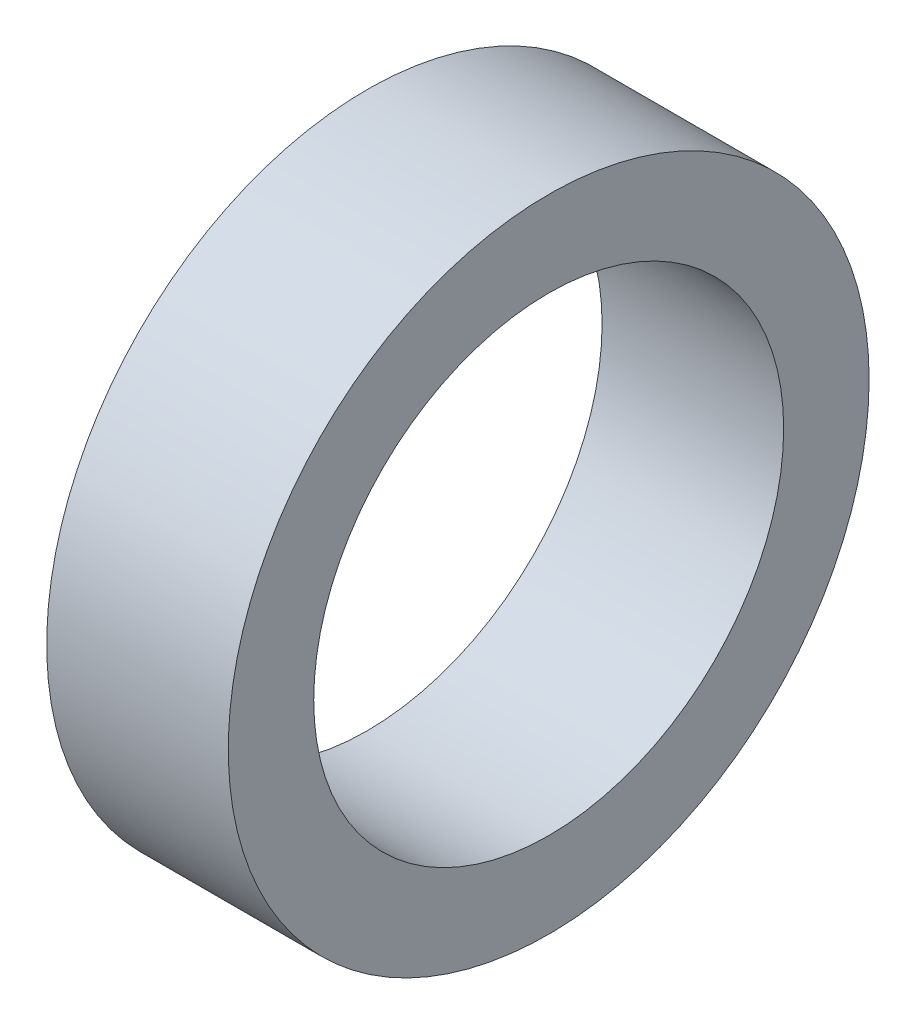
SolidWorks part; units mm, degrees
material "Полиуретан (11671)"
ref_plane "Спереди" through (0, 0, 0) normal (0, 0, 1) x (1, 0, 0)
ref_plane "Сверху" through (0, 0, 0) normal (0, 1, 0) x (1, 0, 0)
ref_plane "Справа" through (0, 0, 0) normal (1, 0, 0) x (0, 0, -1)
sketch "Эскиз1" plane through (0, 0, 0) normal (0, 0, 1) x (1, 0, 0)
  line L0 (-34, 60) -> (-34, 44)
  line L1 (-34, 44) -> (0, 44)
  line L2 (0, 44) -> (0, 60)
  line L3 (0, 60) -> (-34, 60)
  line L4 (-34, 0) -> (0, 0) construction
revolve "Повернуть1" add sketch "Эскиз1" angle 360 about L4
